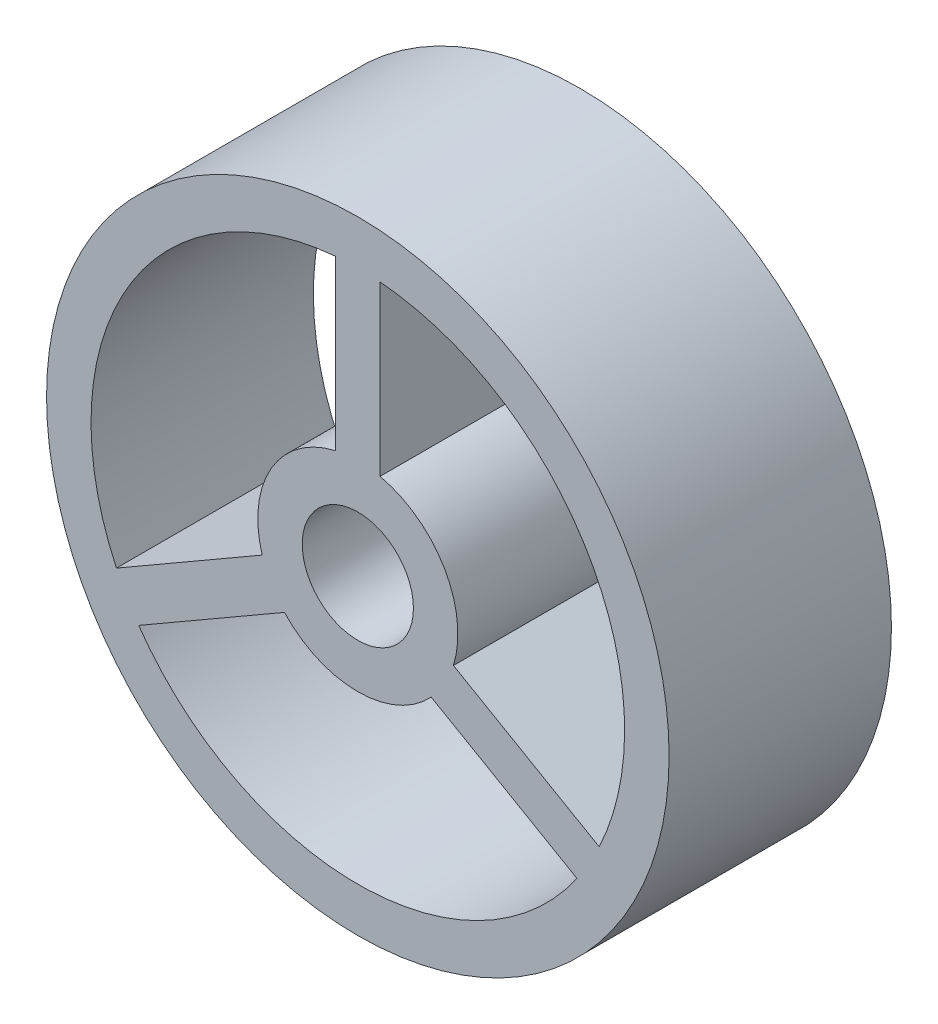
SolidWorks part; units mm, degrees
ref_plane "Front Plane" through (0, 0, 0) normal (0, 0, 1) x (1, 0, 0)
ref_plane "Top Plane" through (0, 0, 0) normal (0, 1, 0) x (1, 0, 0)
ref_plane "Right Plane" through (0, 0, 0) normal (1, 0, 0) x (0, 0, -1)
sketch "Sketch8" plane through (0, 0, 0) normal (0, 0, 1) x (1, 0, 0)
  circle A0 centre (0, 0) radius 14
  dimension "D1" = 28
extrude "Boss-Extrude6" add sketch "Sketch8" along normal blind 10
sketch "Sketch9" plane through (0, 0, 10) normal (0, 0, 1) x (1, 0, 0)
  circle A0 centre (0, 0) radius 2.5
  dimension "D1" = 5
extrude "Cut-Extrude1" cut sketch "Sketch9" against normal blind 10
sketch "Sketch10" plane through (0, 0, 10) normal (0, 0, 1) x (1, 0, 0)
  line L0 (0, 0) -> (0, 12) construction
  line L1 (-1, 4.3875) -> (-1, 11.9583)
  line L2 (1, 4.3875) -> (1, 11.9583)
  line L3 (4.2997, -1.3277) -> (10.8562, -5.1131)
  line L4 (3.2997, -3.0598) -> (9.8562, -6.8452)
  line L5 (-3.2997, -3.0598) -> (-9.8562, -6.8452)
  line L6 (-4.2997, -1.3277) -> (-10.8562, -5.1131)
  circle A0 centre (0, 0) radius 4.5
  circle A1 centre (0, 0) radius 12
  circle A2 centre (0, 0) radius 14 construction
  circle A3 centre (0, 0) radius 2.5 construction
  dimension "D1" = 2
  dimension "D2" = 2
  dimension "D3" = 2
  dimension "D4" = 3
extrude "Cut-Extrude2" cut sketch "Sketch10" against normal blind 10 contours L1 A1 L6 A0 | L3 A1 L2 A0 | L5 A1 L4 A0
